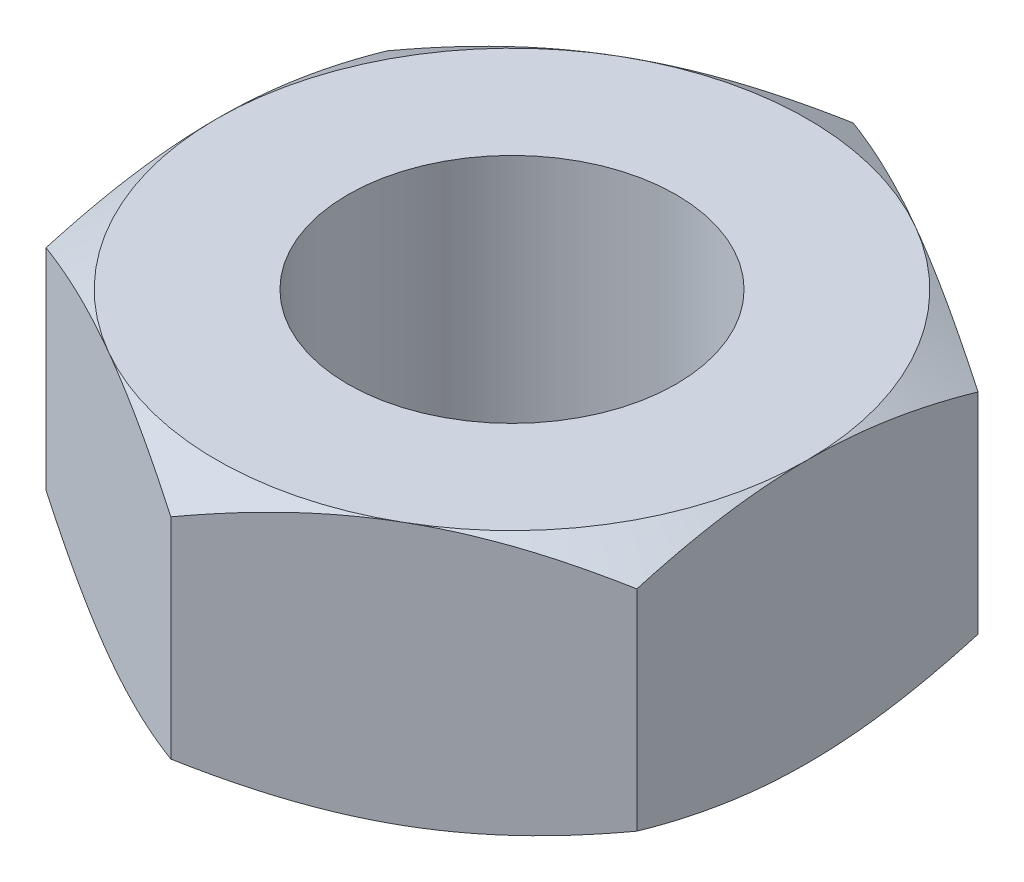
SolidWorks part; units mm, degrees
ref_plane "Front Plane" through (0, 0, 0) normal (0, 0, 1) x (1, 0, 0)
ref_plane "Top Plane" through (0, 0, 0) normal (0, 1, 0) x (1, 0, 0)
ref_plane "Right Plane" through (0, 0, 0) normal (1, 0, 0) x (0, 0, -1)
sketch "Sketch1" plane through (0, 0, 0) normal (0, 1, 0) x (1, 0, 0)
  line L1 (0, 2.5981) -> (-2.25, 1.299)
  line L2 (-2.25, 1.299) -> (-2.25, -1.299)
  line L3 (-2.25, -1.299) -> (0, -2.5981)
  line L4 (0, -2.5981) -> (2.25, -1.299)
  line L5 (2.25, -1.299) -> (2.25, 1.299)
  line L6 (2.25, 1.299) -> (0, 2.5981)
  circle A0 centre (0, 0) radius 1.25
  circle A1 centre (0, 0) radius 2.25 construction
  dimension "D1" = 2.5
  dimension "D2" = 4.5
extrude "Boss-Extrude1" add sketch "Sketch1" along normal blind 2
sketch "Sketch2" plane through (0, 2, 0) normal (0, 1, 0) x (1, 0, 0)
  circle A0 centre (0, 0) radius 2.25 construction
  circle A1 centre (0, 0) radius 2.25
extrude "Cut-Extrude1" cut sketch "Sketch2" against normal blind 2 draft 60 flip side to cut
sketch "Sketch3" plane through (0, 0, 0) normal (0, -1, 0) x (1, 0, 0)
  circle A0 centre (0, 0) radius 2.25 construction
  circle A1 centre (0, 0) radius 2.25
extrude "Cut-Extrude2" cut sketch "Sketch3" against normal blind 2 draft 60 flip side to cut
